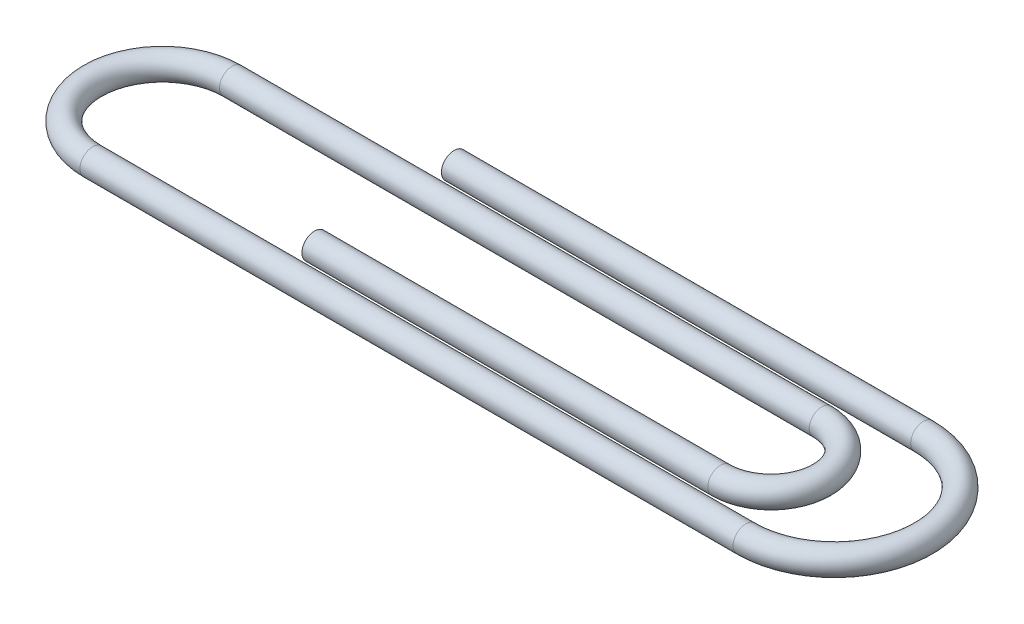
SolidWorks part; units mm, degrees
ref_plane "Front Plane" through (0, 0, 0) normal (0, 0, 1) x (1, 0, 0)
ref_plane "Top Plane" through (0, 0, 0) normal (0, 1, 0) x (1, 0, 0)
ref_plane "Right Plane" through (0, 0, 0) normal (1, 0, 0) x (0, 0, -1)
sketch "Path" plane through (0, 0, 0) normal (0, 1, 0) x (1, 0, 0)
  line L0 (0, 0) -> (18.5, 0)
  line L1 (18.5, -7) -> (-7.25, -7)
  line L2 (-7.25, -1.5) -> (16, -1.5)
  line L3 (16, -5.5) -> (0, -5.5)
  arc A0 (18.5, 0) -> (18.5, -7) centre (18.5, -3.5) cw
  arc A1 (-7.25, -7) -> (-7.25, -1.5) centre (-7.25, -4.25) cw
  arc A2 (16, -1.5) -> (16, -5.5) centre (16, -3.5) cw
  point P11 (18, -3.5)
  point P13 (22, -3.5)
  point P17 (13.7068, -7)
  dimension "D2" = 3.5
  dimension "D6" = 32
  dimension "D1" = 18.5
  dimension "D3" = 1.5
  dimension "D4" = 1.5
  dimension "D5" = 4
  dimension "D7" = 10
sketch "Cross-Section" plane through (0, 0, 0) normal (1, 0, 0) x (0, 0, -1)
  circle A0 centre (0, 0) radius 0.5
  dimension "D1" = 1
sweep "Sweep1" add profiles "Cross-Section" path "Path"
